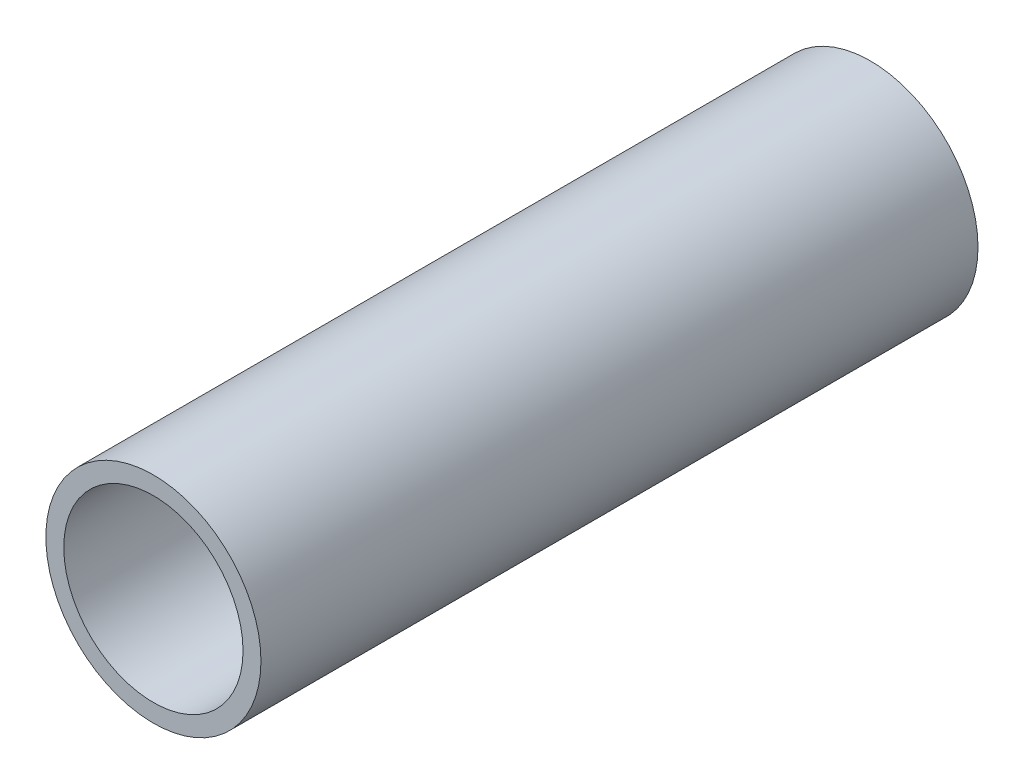
SolidWorks part; units mm, degrees
ref_plane "Płaszczyzna przednia" through (0, 0, 0) normal (0, 0, 1) x (1, 0, 0)
ref_plane "Płaszczyzna górna" through (0, 0, 0) normal (0, 1, 0) x (1, 0, 0)
ref_plane "Płaszczyzna prawa" through (0, 0, 0) normal (1, 0, 0) x (0, 0, -1)
sketch "Szkic1" plane through (0, 0, 0) normal (0, 0, 1) x (1, 0, 0)
  circle A0 centre (0, 0) radius 6
  circle A1 centre (0, 0) radius 5
  dimension "D1" = 10
  dimension "D2" = 12
extrude "Dodanie-wyciągnięcie1" add sketch "Szkic1" along normal blind 40
